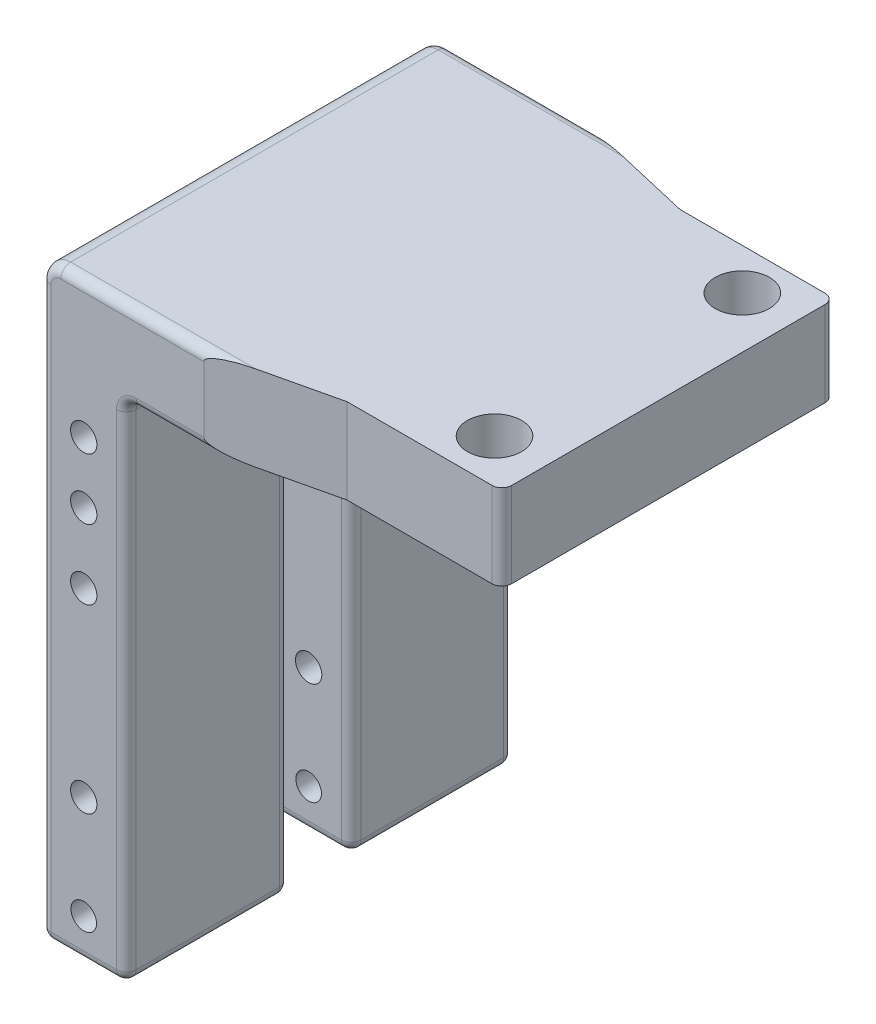
SolidWorks part; units mm, degrees
ref_plane "Front Plane" through (0, 0, 0) normal (0, 0, 1) x (1, 0, 0)
ref_plane "Top Plane" through (0, 0, 0) normal (0, 1, 0) x (1, 0, 0)
ref_plane "Right Plane" through (0, 0, 0) normal (1, 0, 0) x (0, 0, -1)
sketch "Sketch2" plane through (0, 0, 0) normal (0, 1, 0) x (1, 0, 0)
  line L6 (0, 43) -> (0, 0)
  line L7 (0, 0) -> (-20, 0)
  line L8 (-20, 0) -> (-35, -3.5)
  line L9 (-35, -3.5) -> (-45, -3.5)
  line L10 (-45, -3.5) -> (-45, 46.5)
  line L11 (-45, 46.5) -> (-35, 46.5)
  line L12 (-35, 46.5) -> (-20, 43)
  line L13 (-20, 43) -> (0, 43)
  dimension "D1" = 50
  dimension "D2" = 43
  dimension "D3" = 20
  dimension "D4" = 20
  dimension "D5" = 10
  dimension "D6" = 10
  dimension "D7" = 45
extrude "Boss-Extrude1" add sketch "Sketch2" along normal blind 11 contours L13 L6 L7 L8 L9 L10 L11 L12
sketch "Sketch3" plane through (0, 0, 0) normal (0, -1, 0) x (1, 0, 0)
  circle A0 centre (-6.6324, -5.6806) radius 3.5
  circle A2 centre (-6.6315, -37.6806) radius 3.5
  dimension "D2" = 7
  dimension "D3" = 7
  dimension "D1" = 32
extrude "Cut-Extrude1" cut sketch "Sketch3" against normal blind 13
sketch "Sketch5" plane through (-45, 0, 0) normal (-1, 0, 0) x (0, 0, 1)
  line L2 (3.5, 11) -> (3.5, -65.2)
  line L3 (-46.5, 11) -> (3.5, 11)
  line L6 (-25.545, -2.7251) -> (-17.545, -2.7251)
  line L7 (-17.545, -2.7251) -> (-17.545, -65.2)
  line L8 (-17.545, -65.2) -> (3.5, -65.2)
  line L9 (-25.545, -2.7251) -> (-25.545, -65.2)
  line L10 (-25.545, -65.2) -> (-46.5, -65.2)
  line L11 (-46.5, -65.2) -> (-46.5, 11)
  dimension "D1" = 76.2
  dimension "D2" = 20.955
  dimension "D3" = 76.2
  dimension "D5" = 8
  dimension "D6" = 13.7251
extrude "Boss-Extrude2" add sketch "Sketch5" along normal blind 11
sketch "Sketch6" plane through (0, 0, -46.5) normal (0, 0, -1) x (-1, 0, 0)
  line L0 (50.5, -65.2) -> (50.5, 14.2907) construction
  line L1 (56, -65.2) -> (45, -65.2) construction
  line L2 (37.7289, -6.4799) -> (67.2715, -6.4799) construction
  line L3 (37.7289, -23.3683) -> (67.2715, -23.3683) construction
  circle A0 centre (50.5, -6.4799) radius 1.7
  circle A1 centre (50.5, -23.3683) radius 1.7
  circle A2 centre (50.5, -14.3542) radius 1.7
  dimension "D1" = 3.4
  dimension "D2" = 3.4
extrude "Cut-Extrude2" cut sketch "Sketch6" against normal blind 50.8
fillet "Fillet1" radius 2.54 1 edges at (-56, 11, -21.5)
fillet "Fillet2" radius 1.27 1 edges at (-45, 0, -21.5)
fillet "Fillet3" radius 1.27 1 edges at (0, 5.5, 0)
fillet "Fillet4" radius 1.27 1 edges at (0, 5.5, -43)
fillet "Fillet5" radius 1.27 2 edges at (-50.5, -65.2, -17.545) (-50.5, -65.2, -25.545)
fillet "Fillet6" radius 1.27 6 edges at (-56, -65.2, -6.3875) (-56, -64.828, -17.173) (-56, -65.2, -36.6575) (-56, -64.828, -25.917) (-56, -33.3276, -17.545) (-56, -33.3276, -25.545)
fillet "Fillet7" radius 1.27 10 edges at (-44.23, 11, -46.5) (-55.2561, 10.2561, -46.5) (-49.865, -65.2, -46.5) (-55.628, -64.828, -46.5) (-49.865, -65.2, 3.5) (-55.628, -64.828, 3.5) (-44.23, 11, 3.5) (-55.2561, 10.2561, 3.5) (-56, -27.735, -46.5) (-56, -27.735, 3.5)
sketch "Sketch7" plane through (0, 0, -46.5) normal (0, 0, -1) x (-1, 0, 0)
  circle A0 centre (50.5, -60.0416) radius 1.651
  circle A1 centre (50.5, -46.74) radius 1.7
  dimension "D2" = 3.4
  dimension "D3" = 3.302
extrude "Cut-Extrude3" cut sketch "Sketch7" against normal blind 60.96
fillet "Fillet8" radius 1.27 14 edges at (-39.365, 0, -46.5) (-44.628, -0.372, -46.5) (-45, -64.828, -46.128) (-45, -64.828, -25.917) (-45, -64.828, -17.173) (-39.365, 0, 3.5) (-44.628, -0.372, 3.5) (-45, -64.828, 3.128) (-45, -32.6, 3.5) (-45, -33.3276, -17.545) (-45, -33.3276, -25.545) (-45, -32.6, -46.5) (-45, -65.2, -36.0225) (-45, -65.2, -7.0225)
